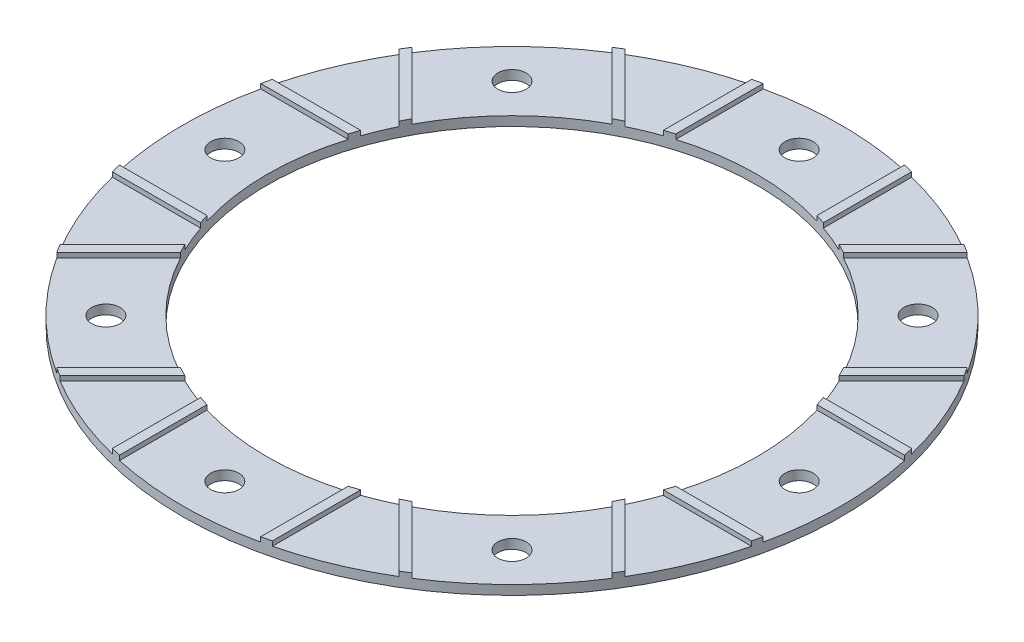
SolidWorks part; units mm, degrees
ref_plane "Спереди" through (0, 0, 0) normal (0, 0, 1) x (1, 0, 0)
ref_plane "Сверху" through (0, 0, 0) normal (0, 1, 0) x (1, 0, 0)
ref_plane "Справа" through (0, 0, 0) normal (1, 0, 0) x (0, 0, -1)
sketch "Эскиз1" plane through (0, 0, 0) normal (0, 1, 0) x (1, 0, 0)
  line L0 (0, 35) -> (0, 26) construction
  circle A0 centre (0, 0) radius 35
  circle A1 centre (0, 0) radius 26
  circle A2 centre (0, 30.5) radius 1.5
  circle A3 centre (21.5668, 21.5668) radius 1.5
  circle A4 centre (30.5, 0) radius 1.5
  circle A5 centre (21.5668, -21.5668) radius 1.5
  circle A6 centre (0, -30.5) radius 1.5
  circle A7 centre (-21.5668, -21.5668) radius 1.5
  circle A8 centre (-30.5, 0) radius 1.5
  circle A9 centre (-21.5668, 21.5668) radius 1.5
  point P24 (0, 0)
  dimension "D1" = 9
  dimension "D2" = 70
  dimension "D3" = 3
  dimension "D4" = 8
extrude "Бобышка-Вытянуть1" add sketch "Эскиз1" along normal blind 1
sketch "Эскиз2" plane through (0, 1, 0) normal (0, 1, 0) x (1, 0, 0)
  line L0 (-8.5, 33.9522) -> (-8.5, 24.5713)
  line L1 (-7.5, 34.187) -> (-7.5, 24.8948)
  line L2 (7.5, 34.187) -> (7.5, 24.8948)
  line L3 (8.5, 33.9522) -> (8.5, 24.5713)
  line L4 (-7.5, 29.5409) -> (7.5, 29.5409) construction
  circle A0 centre (0, 0) radius 35 construction
  circle A1 centre (0, 0) radius 26 construction
  circle A2 centre (0, 0) radius 26
  circle A3 centre (0, 0) radius 35
  circle M7 centre (0, 0) radius 26
  circle M15 centre (0, 0) radius 35
  dimension "D1" = 1
  dimension "D2" = 1
  dimension "D3" = 15
extrude "Бобышка-Вытянуть2" add sketch "Эскиз2" along normal blind 0.5 contours L1 L0 M15 M7 | L3 L2 M15 M7
pattern_circular "Круговой массив1" count 8 every 45 about axis through (0, 0, 0) along (0, 1, 0) of "Бобышка-Вытянуть2"
